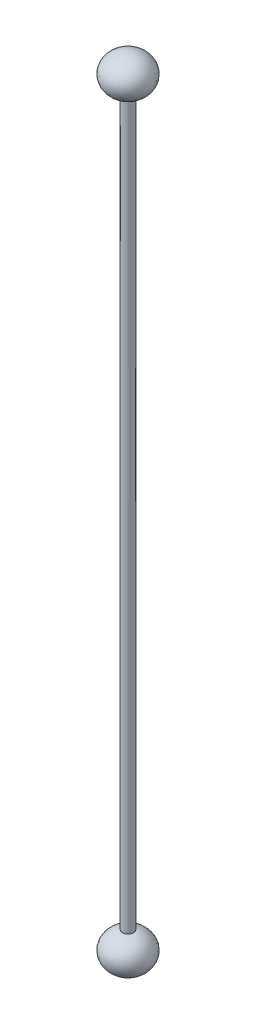
SolidWorks part; units mm, degrees
ref_plane "Front Plane" through (0, 0, 0) normal (0, 0, 1) x (1, 0, 0)
ref_plane "Top Plane" through (0, 0, 0) normal (0, 1, 0) x (1, 0, 0)
ref_plane "Right Plane" through (0, 0, 0) normal (1, 0, 0) x (0, 0, -1)
sketch "Sketch1" plane through (0, 0, 0) normal (0, 0, 1) x (1, 0, 0)
  line L0 (0, -0.7) -> (0, 0)
  line L1 (0, 0) -> (0.75, 0)
  line L2 (0, 0) -> (0, 103)
  line L3 (0, 103) -> (0.75, 103)
  line L4 (0.75, 0) -> (0.75, 103)
  line L5 (0, 105.5) -> (0, 103)
  ellipse E0 centre (0, 103) end of major axis (3, 103) minor radius 2.5 (0, 100.5) -> (0, 105.5) ccw
  point P6 (0, 0)
  point P11 (0, 0)
  point P17 (0, 103.0471)
  point P19 (0, 105.4247)
  dimension "D1" = 0.75
  dimension "D2" = 103
  dimension "D3" = 2.5
  dimension "D5" = 3
revolve "Revolve2" add sketch "Sketch1" angle 360 about L2
ref_plane "Plane1" through (0, 51.5, 0) normal (0, -1, 0) x (-1, 0, 0)
mirror "Mirror1" about plane through (0, 51.5, 0) normal (0, -1, 0) of "Revolve2"
sketch "Sketch2" plane through (0, 0, 0) normal (0, 0, 1) x (1, 0, 0)
  point P0 (0, 103)
  point P1 (0, 0)
